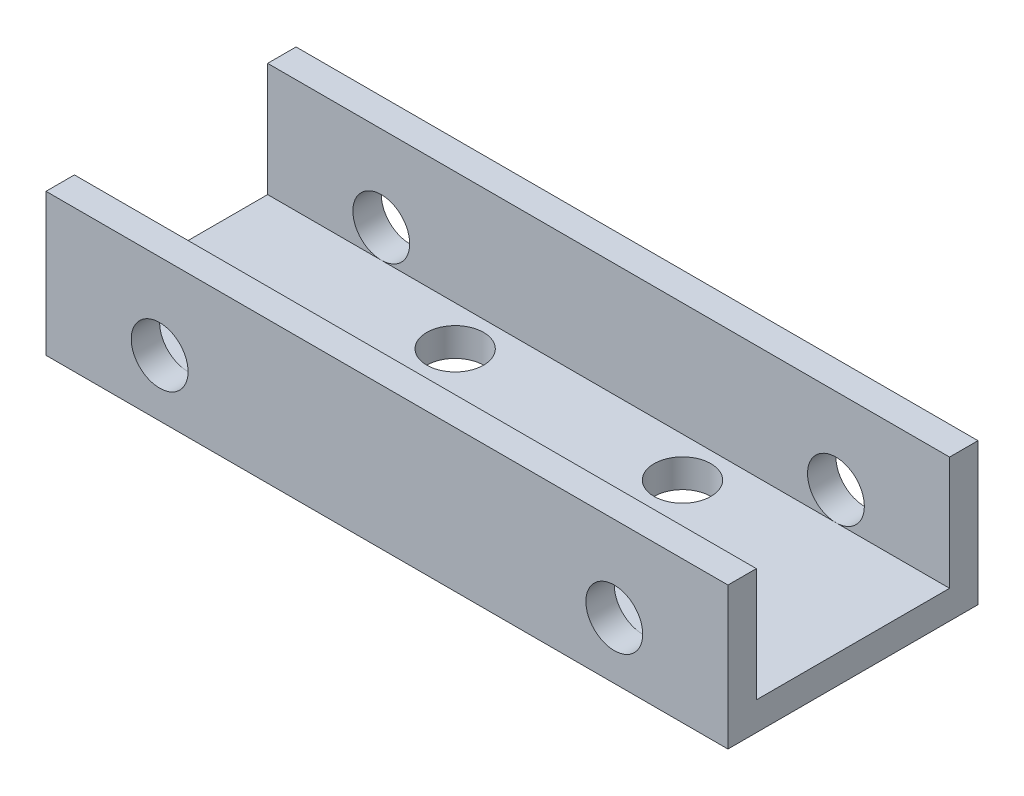
SolidWorks part; units mm, degrees
ref_plane "Front Plane" through (0, 0, 0) normal (0, 0, 1) x (1, 0, 0)
ref_plane "Top Plane" through (0, 0, 0) normal (0, 1, 0) x (1, 0, 0)
ref_plane "Right Plane" through (0, 0, 0) normal (1, 0, 0) x (0, 0, -1)
sketch "Sketch1" plane through (0, 0, 0) normal (0, 1, 0) x (1, 0, 0)
  line L1 (-60, 22) -> (60, 22)
  line L2 (-60, 22) -> (-60, -22)
  line L3 (-60, -22) -> (60, -22)
  line L4 (60, 22) -> (60, -22)
  line L5 (-60, 22) -> (60, -22) construction
  line L6 (-60, -22) -> (60, 22) construction
  point P0 (0, 0)
  dimension "D1" = 44
  dimension "D2" = 120
extrude "Boss-Extrude1" add sketch "Sketch1" along normal blind 5
sketch "Sketch2" plane through (0, 5, 0) normal (0, 1, 0) x (1, 0, 0)
  line L0 (-60, 22) -> (60, 22)
  line L1 (60, 22) -> (60, 17)
  line L2 (60, -22) -> (60, 22) construction
  line L3 (60, 17) -> (-60, 17)
  line L4 (-60, 22) -> (-60, -22) construction
  line L5 (-60, 17) -> (-60, 22)
  line L6 (-60, 0) -> (60, 0) construction
  line L7 (60, -17) -> (-60, -17)
  line L8 (60, -22) -> (60, -17)
  line L9 (-60, -22) -> (60, -22)
  line L10 (-60, -17) -> (-60, -22)
  dimension "D1" = 5
extrude "Boss-Extrude2" add sketch "Sketch2" along normal blind 20 contours L5 L0 L1 L3 | L7 L10 L9 L8
sketch "Sketch3" plane through (0, 0, 22) normal (0, 0, 1) x (1, 0, 0)
  line L0 (-60, 25) -> (-60, 0) construction
  line L1 (-60, 0) -> (60, 0) construction
  line L2 (60, 25) -> (60, 0) construction
  circle A0 centre (40, 10) radius 5
  circle A1 centre (-40, 10) radius 5
  dimension "D1" = 10
  dimension "D2" = 10
  dimension "D3" = 20
  dimension "D4" = 10
  dimension "D5" = 10
  dimension "D6" = 20
extrude "Cut-Extrude1" cut sketch "Sketch3" against normal through all contours A0 | A1
sketch "Sketch4" plane through (0, 5, 0) normal (0, 1, 0) x (1, 0, 0)
  line L0 (-60, 17) -> (-60, -17) construction
  line L1 (60, -17) -> (60, 17) construction
  line L2 (-40, 17) -> (-60, 17) construction
  line L3 (60, -17) -> (-60, -17) construction
  line L4 (60, 17) -> (-60, 17) construction
  line L5 (60, -17) -> (40, -17) construction
  circle A0 centre (20, 10) radius 5
  circle A1 centre (20, -10) radius 5
  circle A2 centre (-20, 10) radius 5
  circle A3 centre (-20, -10) radius 5
  dimension "D1" = 10
  dimension "D2" = 40
  dimension "D3" = 40
  dimension "D4" = 40
  dimension "D5" = 40
  dimension "D6" = 7
  dimension "D7" = 7
  dimension "D8" = 7
  dimension "D9" = 7
extrude "Cut-Extrude3" cut sketch "Sketch4" against normal through all contours A2 | A3 | A1 | A0
